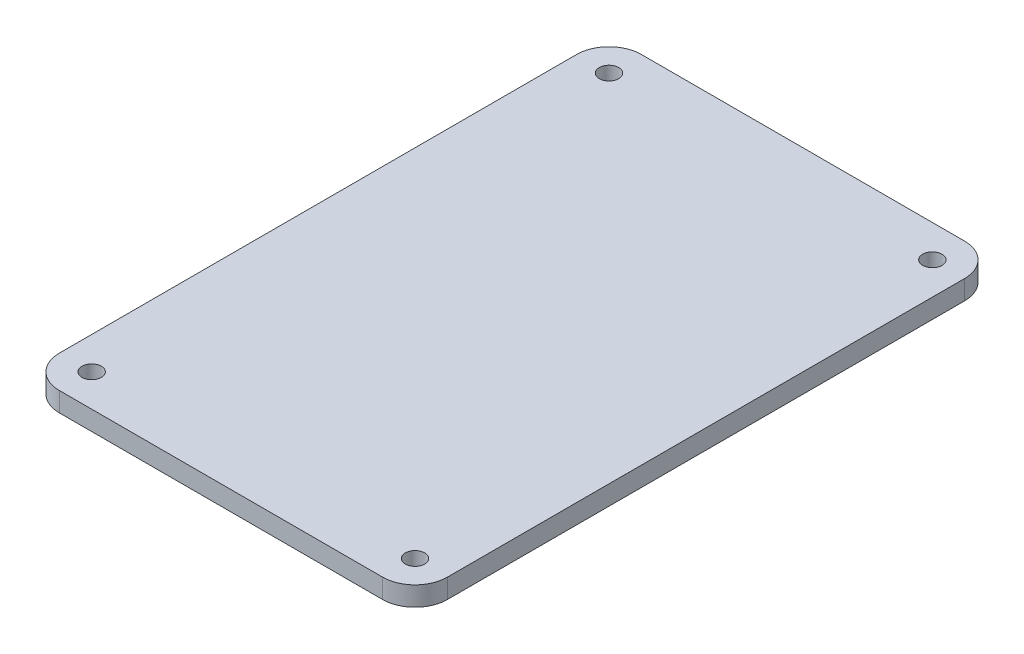
SolidWorks part; units mm, degrees
ref_plane "Front" through (0, 0, 0) normal (0, 0, 1) x (1, 0, 0)
ref_plane "Top" through (0, 0, 0) normal (0, 1, 0) x (1, 0, 0)
ref_plane "Right" through (0, 0, 0) normal (1, 0, 0) x (0, 0, -1)
sketch "草圖1" plane through (0, 0, 0) normal (0, 1, 0) x (1, 0, 0)
  line L1 (-25, -45) -> (25, -45)
  line L2 (-30, -40) -> (-30, 40)
  line L3 (-25, 45) -> (25, 45)
  line L4 (30, -40) -> (30, 40)
  line L5 (-30, -45) -> (30, 45) construction
  line L6 (-30, 45) -> (30, -45) construction
  arc A0 (25, -45) -> (30, -40) centre (25, -40) ccw
  arc A1 (-25, -45) -> (-30, -40) centre (-25, -40) cw
  arc A2 (25, 45) -> (30, 40) centre (25, 40) cw
  arc A3 (-30, 40) -> (-25, 45) centre (-25, 40) cw
  circle A4 centre (-25, 40) radius 1.5
  circle A5 centre (25, 40) radius 1.5
  circle A6 centre (-25, -40) radius 1.5
  circle A7 centre (25, -40) radius 1.5
  point P0 (0, 0)
  dimension "D3" = 5
  dimension "D4" = 3
  dimension "D1" = 90
  dimension "D2" = 60
extrude "填料-伸長1" add sketch "草圖1" along normal blind 3
